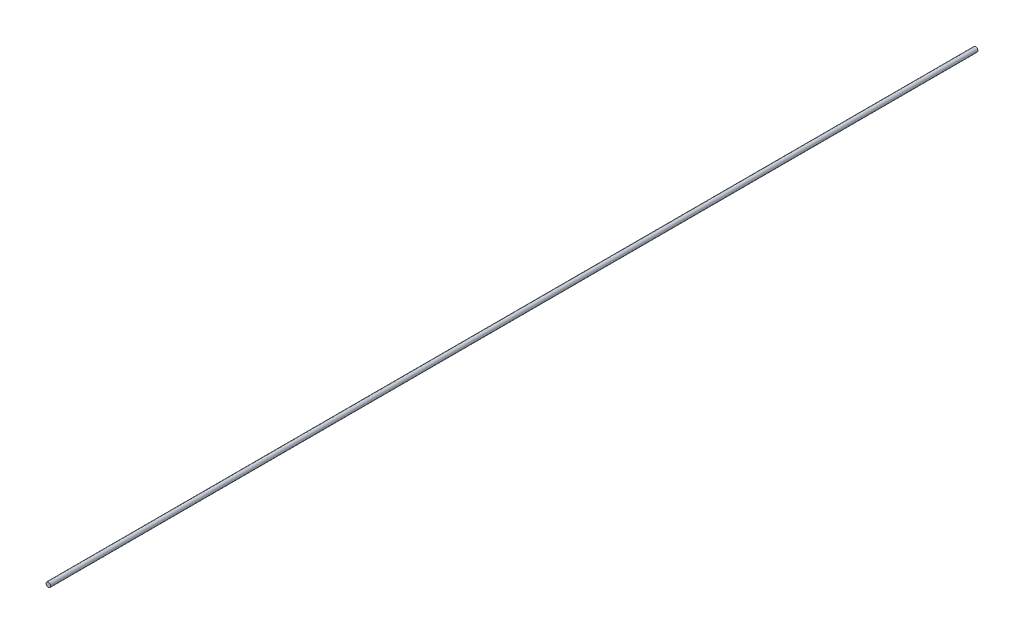
SolidWorks part; units mm, degrees
material "Silicon Dioxide"
ref_plane "Front Plane" through (0, 0, 0) normal (0, 0, 1) x (1, 0, 0)
ref_plane "Top Plane" through (0, 0, 0) normal (0, 1, 0) x (1, 0, 0)
ref_plane "Right Plane" through (0, 0, 0) normal (1, 0, 0) x (0, 0, -1)
sketch "Sketch1" plane through (0, 0, 0) normal (0, 0, 1) x (1, 0, 0)
  circle A0 centre (0, 0) radius 0.35
  dimension "D1" = 0.7
extrude "Boss-Extrude1" add sketch "Sketch1" along normal blind 140
